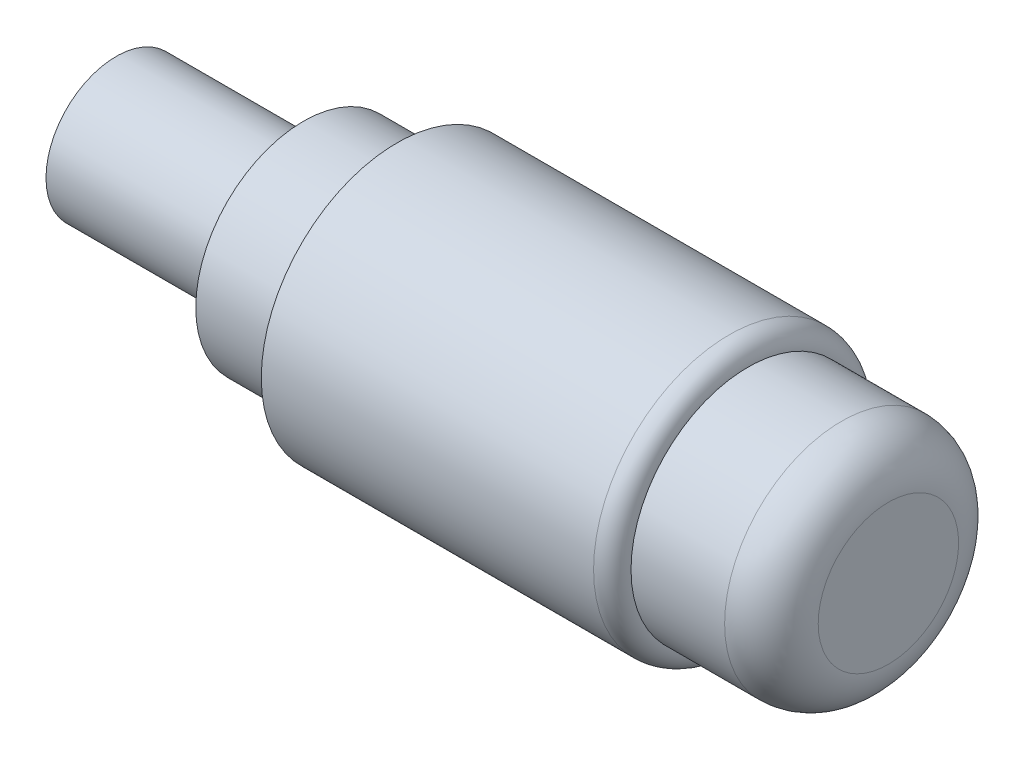
SolidWorks part; units mm, degrees
ref_plane "前视基准面" through (0, 0, 0) normal (0, 0, 1) x (1, 0, 0)
ref_plane "上视基准面" through (0, 0, 0) normal (0, 1, 0) x (1, 0, 0)
ref_plane "右视基准面" through (0, 0, 0) normal (1, 0, 0) x (0, 0, -1)
sketch "草图1" plane through (0, 0, 0) normal (0, 0, 1) x (1, 0, 0)
  line L0 (-9.4044, 0) -> (10.6105, 0) construction
  line L1 (0, 0) -> (0, 1.5)
  line L2 (0, 1.5) -> (4, 1.5)
  line L3 (4, 1.5) -> (4, 2.3)
  line L4 (4, 2.3) -> (6, 2.3)
  line L5 (6, 2.3) -> (6, 2.9)
  line L6 (6, 2.9) -> (13.1, 2.9)
  line L7 (13.5, 2.5) -> (15.5, 2.5)
  line L8 (16.5, 1.5) -> (16.5, 0)
  line L9 (16.5, 0) -> (0, 0)
  arc A0 (13.1, 2.9) -> (13.5, 2.5) centre (13.1, 2.5) cw
  arc A1 (15.5, 2.5) -> (16.5, 1.5) centre (15.5, 1.5) cw
  point P15 (9.4495, 0)
  point P17 (0, 0)
  point P18 (11.8624, 2.5)
  point P19 (16.5, 1.8177)
  dimension "D9" = 1
  dimension "D1" = 16.5
  dimension "D2" = 13.5
  dimension "D3" = 4
  dimension "D4" = 2
  dimension "D5" = 1.5
  dimension "D6" = 2.3
  dimension "D7" = 2.9
  dimension "D8" = 2.5
revolve "旋转1" add sketch "草图1" angle 360 about L0
